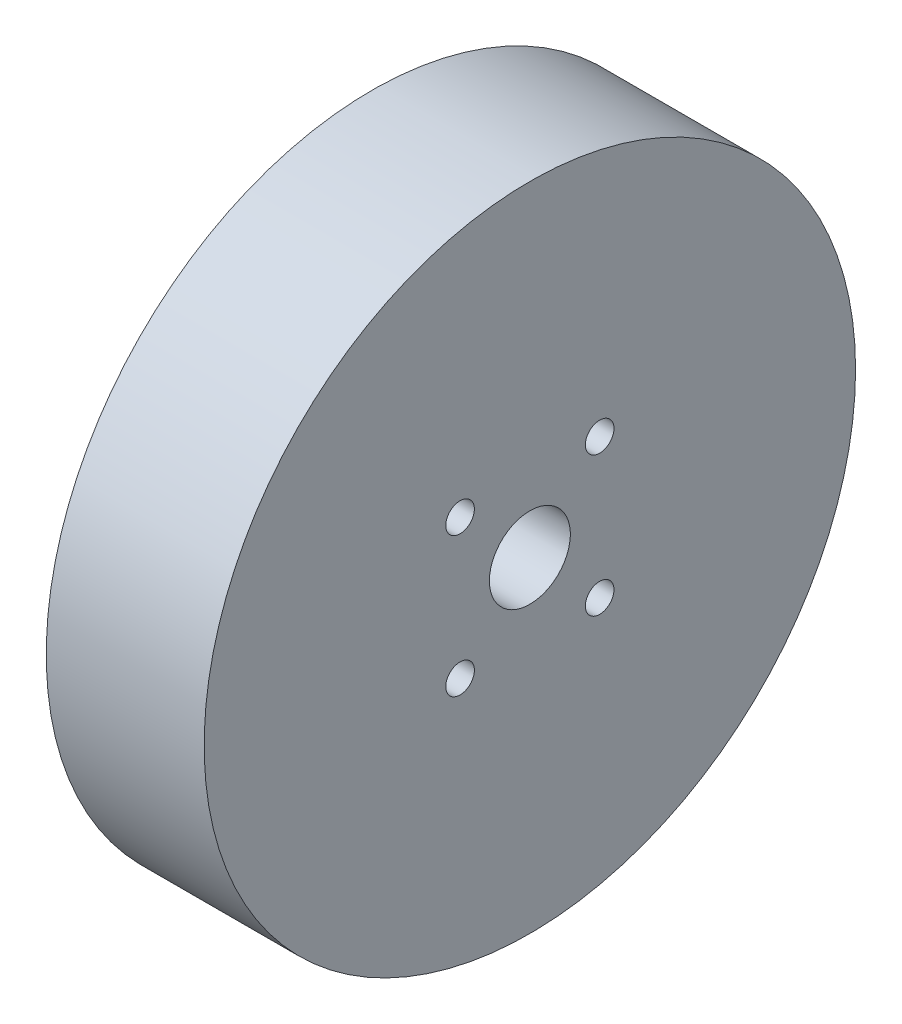
SolidWorks part; units mm, degrees
ref_plane "前视基准面" through (0, 0, 0) normal (0, 0, 1) x (1, 0, 0)
ref_plane "上视基准面" through (0, 0, 0) normal (0, 1, 0) x (1, 0, 0)
ref_plane "右视基准面" through (0, 0, 0) normal (1, 0, 0) x (0, 0, -1)
other "Configuration Table"
sketch "草图1" plane through (0, 0, 0) normal (1, 0, 0) x (0, 0, -1)
  circle A0 centre (0, 0) radius 33
  dimension "D1" = 66
extrude "凸台-拉伸1" add sketch "草图1" along normal blind 16
sketch "草图2" plane through (0, 0, 0) normal (-1, 0, 0) x (0, 0, 1)
  line L0 (0, 0) -> (-7.0711, 7.0711) construction
  line L1 (0, 0) -> (7.0711, 7.0711) construction
  line L2 (0, 0) -> (-7.0711, -7.0711) construction
  line L3 (0, 0) -> (7.0711, -7.0711) construction
  circle A0 centre (0, 0) radius 4.1
  circle A2 centre (-7.0711, 7.0711) radius 1.45
  circle A3 centre (-7.0711, -7.0711) radius 1.45
  circle A4 centre (7.0711, -7.0711) radius 1.45
  circle A5 centre (7.0711, 7.0711) radius 1.45
  dimension "D1" = 8.2
  dimension "D6" = 2.9
  dimension "D2" = 10
  dimension "D3" = 10
  dimension "D4" = 10
  dimension "D5" = 10
extrude "切除-拉伸1" cut sketch "草图2" against normal blind 16
